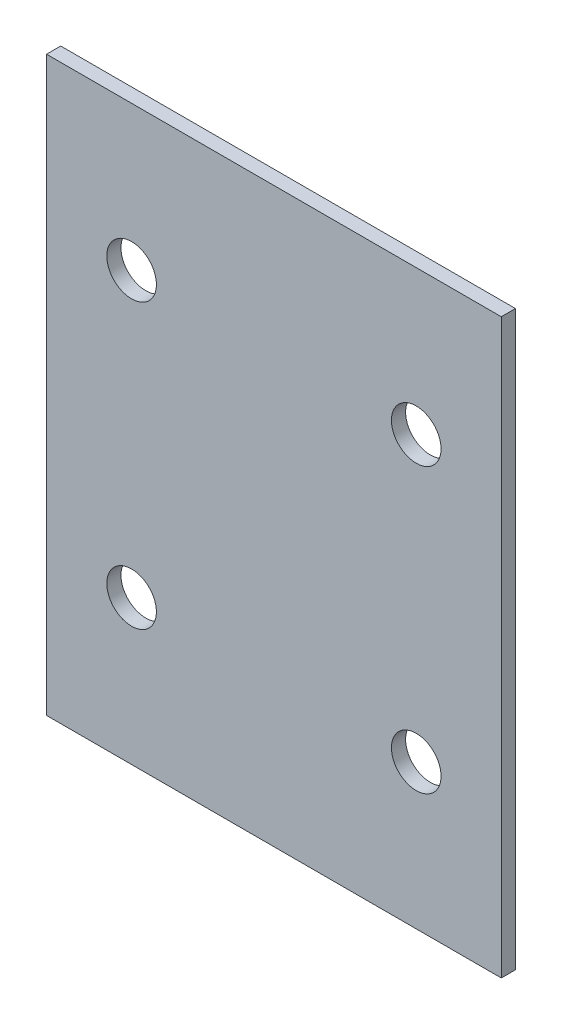
SolidWorks part; units mm, degrees
ref_plane "Front Plane" through (0, 0, 0) normal (0, 0, 1) x (1, 0, 0)
ref_plane "Top Plane" through (0, 0, 0) normal (0, 1, 0) x (1, 0, 0)
ref_plane "Right Plane" through (0, 0, 0) normal (1, 0, 0) x (0, 0, -1)
sketch "Sketch1" plane through (0, 0, 0) normal (0, 0, 1) x (1, 0, 0)
  line L1 (-20.2074, 267.3636) -> (183.5006, 267.3636)
  line L2 (-20.2074, 267.3636) -> (-20.2074, 10.8236)
  line L3 (-20.2074, 10.8236) -> (183.5006, 10.8236)
  line L4 (183.5006, 267.3636) -> (183.5006, 10.8236)
extrude "Boss-Extrude1" add sketch "Sketch1" along normal blind 6.35
sketch "Sketch2" plane through (0, 0, 0) normal (0, 0, -1) x (-1, 0, 0)
  line L0 (-145.4006, 202.5936) -> (-17.8926, 202.5936) construction
  line L1 (-17.8926, 202.5936) -> (-17.8926, 75.5936) construction
  line L2 (-17.8926, 75.5936) -> (-145.4006, 75.5936) construction
  line L3 (-145.4006, 75.5936) -> (-145.4006, 202.5936) construction
  line L4 (-183.5006, 139.0936) -> (20.2074, 139.0936) construction
  line L5 (-183.5006, 10.8236) -> (-183.5006, 267.3636) construction
  line L6 (20.2074, 267.3636) -> (20.2074, 10.8236) construction
  line L7 (-81.6466, 202.5936) -> (-81.6466, 75.5936) construction
  circle A0 centre (-145.4006, 202.5936) radius 11.1125
  circle A1 centre (-145.4006, 75.5936) radius 11.1125
  circle A2 centre (-17.8926, 202.5936) radius 11.1125
  circle A3 centre (-17.8926, 75.5936) radius 11.1125
  point P14 (-81.6466, 139.0936)
  dimension "D1" = 22.225
  dimension "D2" = 38.1
  dimension "D3" = 127
extrude "Cut-Extrude1" cut sketch "Sketch2" against normal up to next
